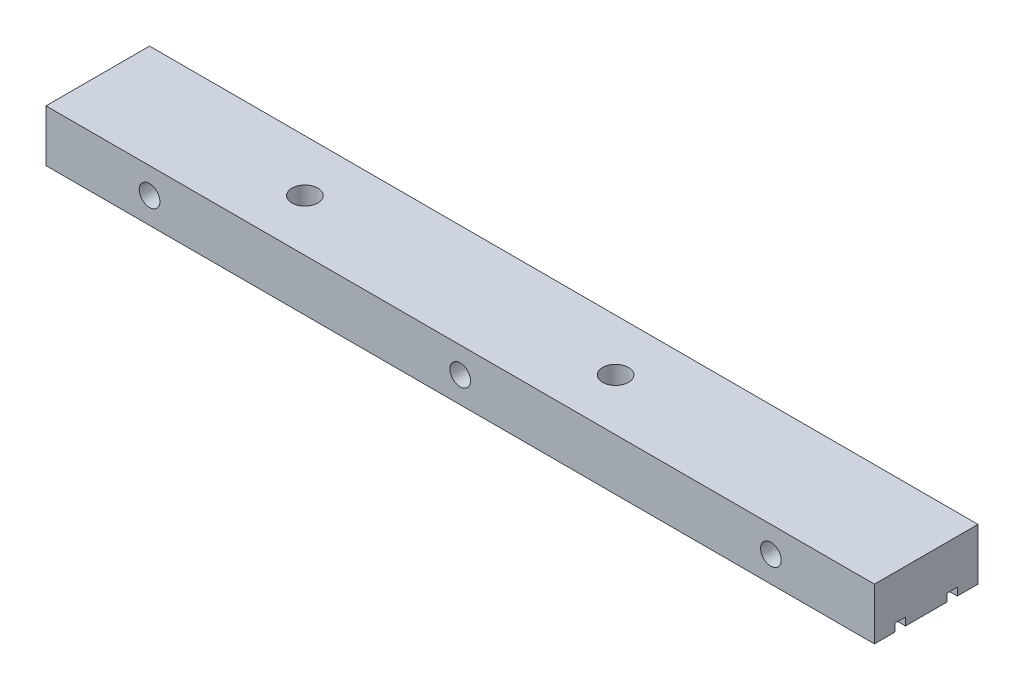
SolidWorks part; units mm, degrees
ref_plane "Ön Düzlem" through (0, 0, 0) normal (0, 0, 1) x (1, 0, 0)
ref_plane "Üst Düzlem" through (0, 0, 0) normal (0, 1, 0) x (1, 0, 0)
ref_plane "Sağ Düzlem" through (0, 0, 0) normal (1, 0, 0) x (0, 0, -1)
sketch "Çizim1" plane through (0, 0, 0) normal (0, 0, 1) x (1, 0, 0)
  line L1 (0, 0) -> (160, 0)
  line L2 (0, 0) -> (0, 10)
  line L3 (0, 10) -> (160, 10)
  line L4 (160, 0) -> (160, 10)
  dimension "D4" = 10
extrude "Yükseklik-Ekstrüzyon1" add sketch "Çizim1" along normal blind 20
sketch "Çizim4" plane through (0, 10, 0) normal (0, 1, 0) x (1, 0, 0)
  line L0 (0, -10) -> (160, -10) construction
  line L1 (0, -20) -> (0, 0) construction
  line L2 (160, -20) -> (160, 0) construction
  line L3 (40, 0) -> (40, -20) construction
  line L4 (160, 0) -> (0, 0) construction
  line L5 (160, -20) -> (0, -20) construction
  line L6 (120, 0) -> (120, -20) construction
  point P16 (40, -10)
  point P17 (100, -10)
  dimension "D1" = 40
  dimension "D2" = 40
hole_wizard "Ø4.0mm Saplama Delikleri1" positions "3B Çizim3" profile "Çizim5" hole size "Ø4.0" standard "ANSI Metric"
sketch3d "3B Çizim3"
  point P0 (40, 10, 10)
  point P3 (100, 10, 10)
  point P6 (0, 0, 0)
  point P7 (100, 10, 10)
  point P8 (100, 10, 10)
sketch "Çizim5" plane through (40, 10, 10) normal (1, 0, 0) x (0, 0, 1)
  line L0 (0, 0) -> (0, 8)
  line L1 (0, 8) -> (2.5, 8)
  line L2 (2.5, 8) -> (2.5, 0)
  line L5 (2.5, 0) -> (0, 0)
  line L10 (0, 8) -> (-2.5, 8) construction
  line L11 (0, -6.35) -> (0, 107.95) construction
  dimension "Hole Dia." = 5
  dimension "Hole Depth" = 8
  dimension "Drill Angle" = 180
sketch "Çizim6" plane through (0, 0, 0) normal (-1, 0, 0) x (0, 0, 1)
  line L0 (20, 0) -> (0, 0) construction
  line L1 (0, 10) -> (0, 0) construction
  line L2 (4, 0) -> (6, 0)
  line L3 (4, 0) -> (4, 1.5)
  line L4 (4, 1.5) -> (6, 1.5)
  line L5 (6, 0) -> (6, 1.5)
  line L6 (14, 0) -> (16, 0)
  line L7 (14, 0) -> (14, 1.5)
  line L8 (14, 1.5) -> (16, 1.5)
  line L9 (16, 0) -> (16, 1.5)
  line L10 (20, 10) -> (20, 0) construction
  dimension "D1" = 4
  dimension "D2" = 4
  dimension "D3" = 2
  dimension "D4" = 2
  dimension "D5" = 1.5
extrude "Kes-Ekstrüzyon1" cut sketch "Çizim6" against normal through all
sketch "Çizim7" plane through (0, 0, 0) normal (0, 0, -1) x (-1, 0, 0)
  line L0 (-160, 5) -> (0, 5) construction
  line L1 (-160, 0) -> (-160, 10) construction
  line L2 (0, 10) -> (0, 0) construction
  point P6 (-140, 5)
  point P7 (-80, 5)
  point P8 (-20, 5)
  dimension "D1" = 20
  dimension "D2" = 20
hole_wizard "M5 Altıgen Başlı Cıvata İçin Havşa1" positions "3B Çizim4" profile "Çizim8" counterbore size "M5" standard "ANSI Metric" end condition through all
sketch3d "3B Çizim4"
  point P0 (140, 5, 0)
  point P3 (80, 5, 0)
  point P6 (20, 5, 0)
sketch "Çizim8" plane through (140, 5, 0) normal (1, 0, 0) x (0, 1, 0)
  line L0 (0, 0) -> (0, 20)
  line L1 (0, 20) -> (2, 20)
  line L3 (2, 20) -> (2, 6)
  line L4 (2, 6) -> (3.25, 6)
  line L5 (3.25, 6) -> (3.25, 0)
  line L7 (3.25, 0) -> (0, 0)
  line L11 (0, -6.35) -> (0, 107.95) construction
  dimension "Thru Hole Dia." = 4
  dimension "Thru Hole Depth" = 20
  dimension "C'Bore Dia." = 6.5
  dimension "C'Bore Depth" = 6
